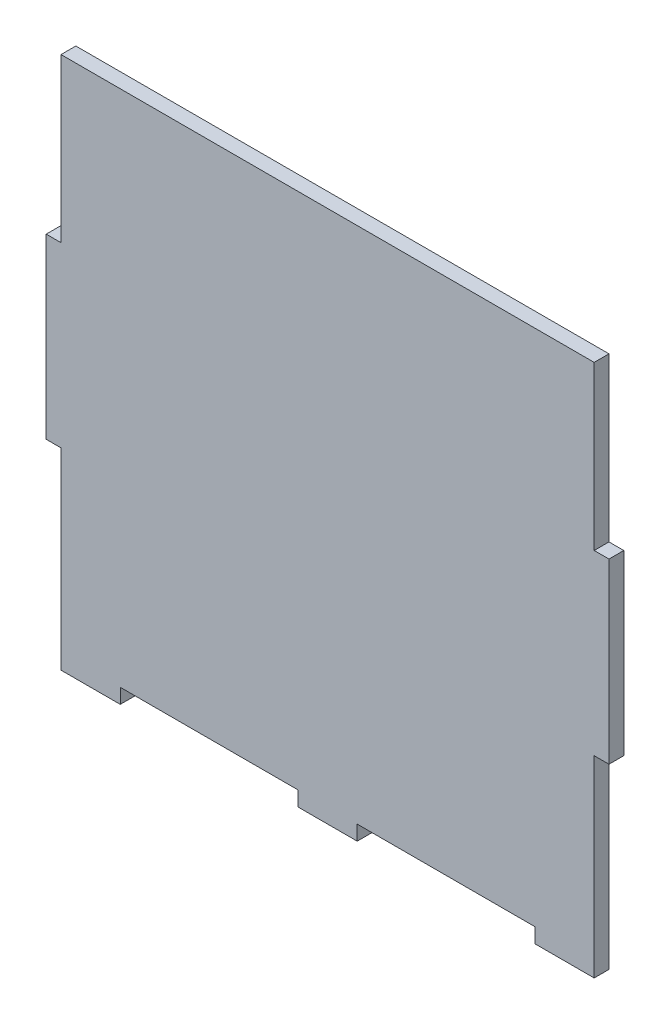
SolidWorks part; units mm, degrees
ref_plane "Front Plane" through (0, 0, 0) normal (0, 0, 1) x (1, 0, 0)
ref_plane "Top Plane" through (0, 0, 0) normal (0, 1, 0) x (1, 0, 0)
ref_plane "Right Plane" through (0, 0, 0) normal (1, 0, 0) x (0, 0, -1)
sketch "Sketch1" plane through (0, 0, 0) normal (0, 0, 1) x (1, 0, 0)
  line L0 (5.2443, 179.9842) -> (5.2443, -48.6158) construction
  line L1 (-109.0557, 179.9842) -> (119.5443, 179.9842)
  line L2 (-109.0557, 179.9842) -> (-109.0557, -48.6158)
  line L3 (-109.0557, -48.6158) -> (-83.6557, -48.6158)
  line L4 (119.5443, 179.9842) -> (119.5443, -48.6158)
  line L5 (-109.0557, 65.6842) -> (119.5443, 65.6842) construction
  line L6 (125.8943, 33.9342) -> (119.5443, 33.9342)
  line L7 (-115.4057, 110.1342) -> (-109.0557, 110.1342)
  line L8 (-115.4057, 110.1342) -> (-115.4057, 33.9342)
  line L9 (-115.4057, 33.9342) -> (-109.0557, 33.9342)
  line L11 (-7.4557, -48.6158) -> (5.2443, -48.6158)
  line L12 (94.1443, -48.6158) -> (94.1443, -42.2658)
  line L13 (-83.6557, -48.6158) -> (-83.6557, -42.2658)
  line L14 (-83.6557, -42.2658) -> (-7.4557, -42.2658)
  line L15 (125.8943, 110.1342) -> (125.8943, 33.9342)
  line L16 (125.8943, 110.1342) -> (119.5443, 110.1342)
  line L23 (-7.4557, -48.6158) -> (-7.4557, -42.2658)
  line L24 (94.1443, -42.2658) -> (17.9443, -42.2658)
  line L25 (17.9443, -48.6158) -> (17.9443, -42.2658)
  line L26 (17.9443, -48.6158) -> (5.2443, -48.6158)
  line L27 (119.5443, -48.6158) -> (94.1443, -48.6158)
  point P29 (-83.6557, -45.4408)
  dimension "D1" = 228.6
  dimension "D2" = 228.6
  dimension "D3" = 6.35
  dimension "D4" = 76.2
  dimension "D6" = 25.4
  dimension "D5" = 82.55
  dimension "D7" = 6.35
  dimension "D8" = 25.4
extrude "Boss-Extrude1" add sketch "Sketch1" along normal blind 6.35 contours L27 L4 L1 L2 L3 L13 L14 L23 L11 L26 L25 L24 L12 | L8 L9 L2 L7 | L15 L16 L4 L6
equation "\"width\"= 9in"
equation "\"Height\"= 18in"
equation "\"thick\"= 0.25"
equation "\"D1@Sketch1\"=\"width\""
equation "\"D3@Sketch1\"=\"thick\""
equation "\"D1@Boss-Extrude1\"=\"thick\""
equation "\"D7@Sketch1\"=\"thick\""
equation "\"D2@Sketch1\"=\"width\""
